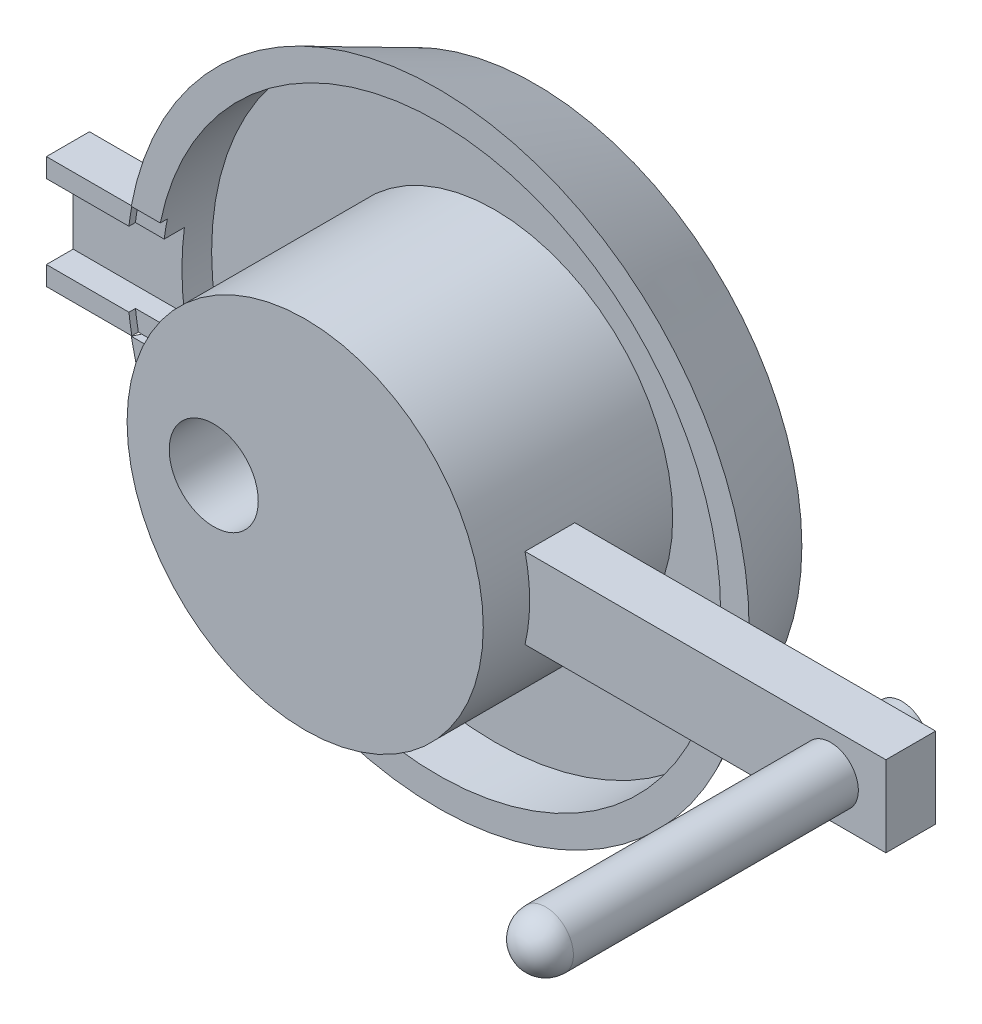
SolidWorks part; units mm, degrees
ref_plane "前视基准面" through (0, 0, 0) normal (0, 0, 1) x (1, 0, 0)
ref_plane "上视基准面" through (0, 0, 0) normal (0, 1, 0) x (1, 0, 0)
ref_plane "右视基准面" through (0, 0, 0) normal (1, 0, 0) x (0, 0, -1)
other "Configuration Table"
sketch "草图1" plane through (0, 0, 0) normal (0, 0, 1) x (1, 0, 0)
  circle A0 centre (0, 0) radius 50
  dimension "D1" = 100
extrude "凸台-拉伸1" add sketch "草图1" along normal mid plane 40
sketch "草图4" plane through (0, 0, 20) normal (0, 0, 1) x (1, 0, 0)
  circle A0 centre (-25.6736, -0.8528) radius 12.5
  dimension "D1" = 25
extrude "切除-拉伸1" cut sketch "草图4" against normal blind 40
ref_plane "基准面1" through (50, 0, 0) normal (1, 0, 0) x (0, 0, -1)
sketch "草图5" plane through (50, 0, 0) normal (1, 0, 0) x (0, 0, -1)
  line L9 (-6.9801, 11.32) -> (6.9801, 11.32)
  line L10 (-6.9801, 11.32) -> (-6.9801, -11.32)
  line L11 (-6.9801, -11.32) -> (6.9801, -11.32)
  line L12 (6.9801, 11.32) -> (6.9801, -11.32)
  line L13 (-6.9801, 11.32) -> (6.9801, -11.32) construction
  line L14 (-6.9801, -11.32) -> (6.9801, 11.32) construction
  point P0 (0, 0)
extrude "凸台-拉伸2" add sketch "草图5" against normal up to surface (72.8324 mm away)
sketch "草图6" plane through (50, 0, 0) normal (1, 0, 0) x (0, 0, -1)
  line L1 (-6.9801, 11.32) -> (6.9801, 11.32)
  line L2 (-6.9801, 11.32) -> (-6.9801, -11.32)
  line L3 (-6.9801, -11.32) -> (6.9801, -11.32)
  line L4 (6.9801, 11.32) -> (6.9801, -11.32)
  line L5 (-6.9801, 11.32) -> (6.9801, -11.32) construction
  line L6 (-6.9801, -11.32) -> (6.9801, 11.32) construction
  point P0 (0, 0)
extrude "凸台-拉伸3" add sketch "草图6" along normal blind 100
sketch "草图7" plane through (0, 0, 6.9801) normal (0, 0, 1) x (1, 0, 0)
  circle A0 centre (134.4965, 0) radius 7.7823
extrude "凸台-拉伸4" add sketch "草图7" along normal blind 80 and the other way blind 20
sketch "草图8" plane through (0, 0, 86.9801) normal (0, 0, 1) x (1, 0, 0)
  line L0 (126.7142, 0) -> (142.2789, 0)
  circle A0 centre (134.4965, 0) radius 7.7823 construction
  circle A1 centre (134.4965, 0) radius 7.7823 construction
  arc A2 (126.7142, 0) -> (142.2789, 0) centre (134.4965, 0) ccw
revolve "旋转1" add sketch "草图8" angle 360 about L0
sketch "草图10" plane through (0, 0, 0) normal (0, 1, 0) x (1, 0, 0)
  line L0 (0, 20) -> (0, 44.4834)
  line L1 (50, 20) -> (-50, 20) construction
  line L2 (0, 44.4834) -> (74.9521, 44.4834)
  line L3 (74.9521, 44.4834) -> (87.4533, 17.1783)
  line L4 (87.4533, 17.1783) -> (50, 17.1783)
  line L5 (50, 6.9801) -> (50, 20) construction
  line L6 (50, 17.1783) -> (50, 20)
  line L7 (50, 20) -> (0, 20)
revolve "旋转2" add sketch "草图10" angle 360 about L0
sketch "草图13" plane through (0, 0, -17.1783) normal (0, 0, 1) x (1, 0, 0)
  circle A0 centre (0, 0) radius 79.4517
extrude "切除-拉伸2" cut sketch "草图13" against normal blind 16 contours A0
sketch "草图14" plane through (0, 0, -33.1783) normal (0, 0, 1) x (1, 0, 0)
  circle A0 centre (0, 0) radius 50
extrude "凸台-拉伸5" add sketch "草图14" along normal blind 16
ref_plane "基准面2" through (-60, 0, 0) normal (-1, 0, 0) x (0, 0, 1)
sketch "草图17" plane through (-60, 0, 0) normal (-1, 0, 0) x (0, 0, 1)
  line L1 (-29.437, 15.803) -> (-17.3473, 15.803)
  line L2 (-29.437, 15.803) -> (-29.437, -15.803)
  line L3 (-29.437, -15.803) -> (-17.3473, -15.803)
  line L4 (-17.3473, 15.803) -> (-17.3473, -15.803)
  line L5 (-29.437, 15.803) -> (-17.3473, -15.803) construction
  line L6 (-29.437, -15.803) -> (-17.3473, 15.803) construction
  point P0 (-23.3921, 0)
extrude "凸台-拉伸6" add sketch "草图17" along normal blind 50
sketch "草图18" plane through (0, 0, -17.3473) normal (0, 0, 1) x (1, 0, 0)
  line L0 (-77.8642, 15.803) -> (-60, 15.803)
  line L1 (-60, 15.803) -> (-60, -15.803)
  line L2 (-60, -15.803) -> (-77.8642, -15.803)
  arc A0 (-77.8642, 15.803) -> (-77.8642, -15.803) centre (0, 0) ccw
extrude "切除-拉伸3" cut sketch "草图18" against normal up to surface (15.831 mm away) up to face at (50, 0, -33.1783)
sketch "草图25" plane through (-110, 0, 0) normal (-1, 0, 0) x (0, 0, 1)
  line L0 (-17.3473, -15.803) -> (-17.3473, 15.803) construction
  line L1 (-24.8504, 10.4411) -> (-17.3473, 10.4411)
  line L2 (-24.8504, 10.4411) -> (-24.8504, -10.4411)
  line L3 (-24.8504, -10.4411) -> (-17.3473, -10.4411)
  line L4 (-17.3473, 10.4411) -> (-17.3473, -10.4411)
  line L5 (-24.8504, 10.4411) -> (-17.3473, -10.4411) construction
  line L6 (-24.8504, -10.4411) -> (-17.3473, 10.4411) construction
  point P0 (-21.0989, 0)
extrude "切除-拉伸4" cut sketch "草图25" against normal up to surface (31.2374 mm away)
sketch "草图26" plane through (0, 0, -17.1783) normal (0, 0, 1) x (1, 0, 0)
  line L0 (-86.0127, 15.8077) -> (-77.8633, 15.8077)
  line L1 (-86.0127, -15.8077) -> (-77.8633, -15.8077)
  circle A2 centre (0, 0) radius 87.4533 construction
  circle A3 centre (0, 0) radius 79.4517 construction
  arc A4 (-86.0127, 15.8077) -> (-86.0127, -15.8077) centre (0, 0) ccw
  arc A5 (-77.8633, 15.8077) -> (-77.8633, -15.8077) centre (0, 0) ccw
extrude "切除-拉伸5" cut sketch "草图26" against normal blind 2
sketch "草图27" plane through (50, 0, 0) normal (1, 0, 0) x (0, 0, -1)
  line L1 (-6.9801, 11.32) -> (6.9801, 11.32)
  line L2 (-6.9801, 11.32) -> (-6.9801, -11.32)
  line L3 (-6.9801, -11.32) -> (6.9801, -11.32)
  line L4 (6.9801, 11.32) -> (6.9801, -11.32)
  line L5 (-6.9801, 11.32) -> (6.9801, -11.32) construction
  line L6 (-6.9801, -11.32) -> (6.9801, 11.32) construction
  point P0 (0, 0)
extrude "凸台-拉伸7" add sketch "草图27" against normal blind 40
